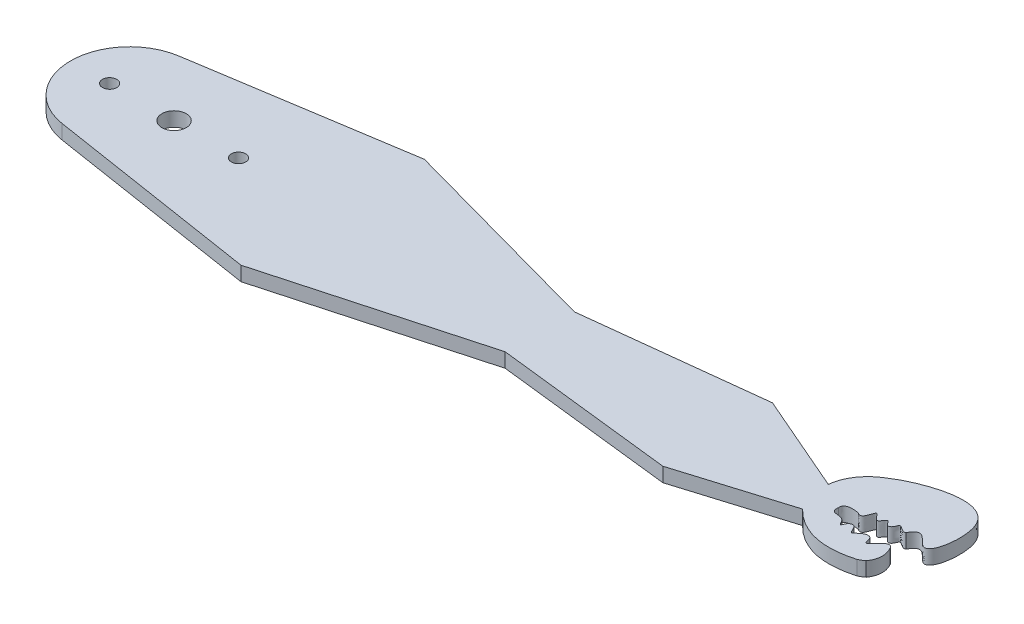
SolidWorks part; units mm, degrees
ref_plane "前视基准面" through (0, 0, 0) normal (0, 0, 1) x (1, 0, 0)
ref_plane "上视基准面" through (0, 0, 0) normal (0, 1, 0) x (1, 0, 0)
ref_plane "右视基准面" through (0, 0, 0) normal (1, 0, 0) x (0, 0, -1)
other "Configuration Table"
sketch "草图3" plane through (0, 0, 0) normal (0, 1, 0) x (1, 0, 0)
  line L0 (-351.5502, 0) -> (-342.5502, 0) construction
  line L1 (-320.3995, 12.806) -> (-291.4793, 4.8295)
  line L3 (-320.3995, -12.8061) -> (-291.4793, -4.8296)
  line L9 (-291.4793, -4.8296) -> (-266.64, -7.6598)
  line L10 (-291.4793, 4.8295) -> (-266.64, 7.6597)
  line L11 (-320.3995, 12.806) -> (-350.0372, 8.1581)
  line L14 (-320.3995, -12.8061) -> (-350.0372, -8.1582)
  line L23 (-342.5502, 0) -> (-342.5502, -12.4691) construction
  line L27 (-266.64, 7.6597) -> (-252.8776, 1.6936)
  line L28 (-266.64, -7.6598) -> (-251.6961, -3.0894)
  arc A1 (-350.0372, -8.1582) -> (-350.0372, 8.1581) centre (-348.7578, 0) cw
  circle A7 centre (-351.5502, 0) radius 1
  circle A8 centre (-342.5502, 0) radius 1.7
  circle A9 centre (-333.5502, 0) radius 1
  spline S0 degree 3 poles (-252.8776, 1.6936) (-252.6649, 3.8966) (-251.1399, 5.7357) (-249.1825, 6.7683) knots 0 0 0 0 0.432418 0.432418 0.432418 0.432418
  spline S1 degree 3 poles (-251.6961, -3.0894) (-249.0847, -5.7496) (-245.7932, -6.5115) (-241.8216, -5.3753) knots 0.135882 0.135882 0.135882 0.135882 1 1 1 1
  spline S2 degree 3 poles (-241.8216, -5.3753) (-241.6432, -5.3094) (-241.3125, -5.1261) (-240.9971, -4.8913) knots 0 0 0 0 0.023628 0.023628 0.023628 0.023628
  spline S3 degree 3 poles (-249.1825, 6.7683) (-247.1921, 8.1222) (-235.3381, 13.1849) (-237.8224, -2.3526) (-240.5902, 3.3466) (-241.615, 1.2791) knots 0 0 0 0 0.564814 0.840388 1 1 1 1
  spline S4 degree 3 poles (-241.615, 1.2791) (-241.6814, 1.2455) (-242.1338, 1.1169) (-242.9511, 2.1413) (-243.1209, 1.0983) (-243.8573, 0.5713) (-244.3687, 2.0498) (-245.0894, 0.0041) (-246.354, 2.8682) (-246.3344, -0.3671) (-247.3112, 0.3235) knots 0.107491 0.107491 0.107491 0.107491 0.132484 0.269585 0.342844 0.409355 0.511314 0.627418 0.767319 1 1 1 1
  spline S5 degree 3 poles (-247.3112, 0.3235) (-247.7071, 0.4379) (-249.5302, 0.6859) (-249.3572, -0.4187) knots 0 0 0 0 1 1 1 1
  spline S6 degree 3 poles (-249.3572, -0.4187) (-249.5159, -1.8046) (-247.8354, -0.679) (-247.1124, -2.7389) (-246.9004, -1.5454) (-245.7898, -1.2922) (-245.567, -2.9907) (-244.721, -1.8028) (-243.3557, -1.4166) (-243.3269, -3.2625) (-242.2242, -1.7973) (-241.1694, -0.9608) (-240.8079, -1.8004) knots 0 0 0 0 0.201321 0.267961 0.329699 0.38879 0.491585 0.554912 0.664187 0.739491 0.84413 0.967687 0.967687 0.967687 0.967687
  spline S7 degree 2 poles (-240.8079, -1.8004) (-239.9669, -3.392) (-240.9971, -4.8913) knots 0 0 0 1 1 1
  dimension "D1" = 9
extrude "凸台-拉伸1" add sketch "草图3" along normal blind 2
